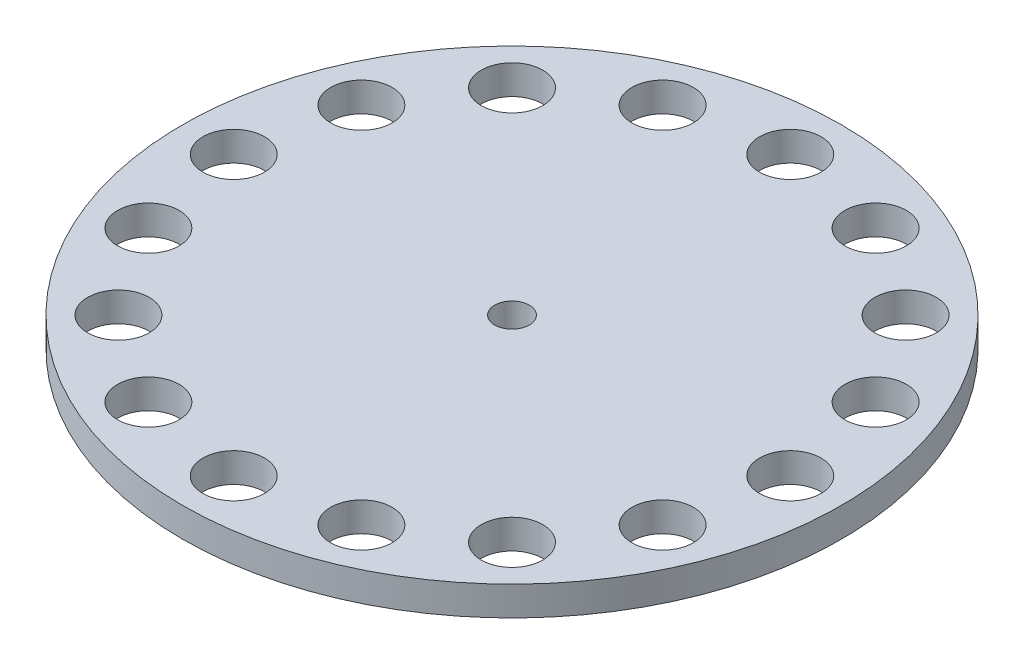
SolidWorks part; units mm, degrees
ref_plane "Front Plane" through (0, 0, 0) normal (0, 0, 1) x (1, 0, 0)
ref_plane "Top Plane" through (0, 0, 0) normal (0, 1, 0) x (1, 0, 0)
ref_plane "Right Plane" through (0, 0, 0) normal (1, 0, 0) x (0, 0, -1)
sketch "Sketch1" plane through (0, 0, 0) normal (0, 1, 0) x (1, 0, 0)
  circle A0 centre (0, 0) radius 57.15
  circle A1 centre (0, 0) radius 2.9972
  circle A2 centre (0, 48.26) radius 5.334
  circle A3 centre (18.4683, 44.5864) radius 5.334
  circle A4 centre (34.125, 34.125) radius 5.334
  circle A5 centre (44.5864, 18.4683) radius 5.334
  circle A6 centre (48.26, 0) radius 5.334
  circle A7 centre (44.5864, -18.4683) radius 5.334
  circle A8 centre (34.125, -34.125) radius 5.334
  circle A9 centre (18.4683, -44.5864) radius 5.334
  circle A10 centre (0, -48.26) radius 5.334
  circle A11 centre (-18.4683, -44.5864) radius 5.334
  circle A12 centre (-34.125, -34.125) radius 5.334
  circle A13 centre (-44.5864, -18.4683) radius 5.334
  circle A14 centre (-48.26, 0) radius 5.334
  circle A15 centre (-44.5864, 18.4683) radius 5.334
  circle A16 centre (-34.125, 34.125) radius 5.334
  circle A17 centre (-18.4683, 44.5864) radius 5.334
  point P7 (-25.4432, 46.5479)
  point P38 (0, 0)
  dimension "D1" = 114.3
  dimension "D2" = 5.9944
  dimension "D3" = 10.668
  dimension "D4" = 48.26
  dimension "D5" = 16
extrude "Boss-Extrude1" add sketch "Sketch1" along normal blind 5.08
